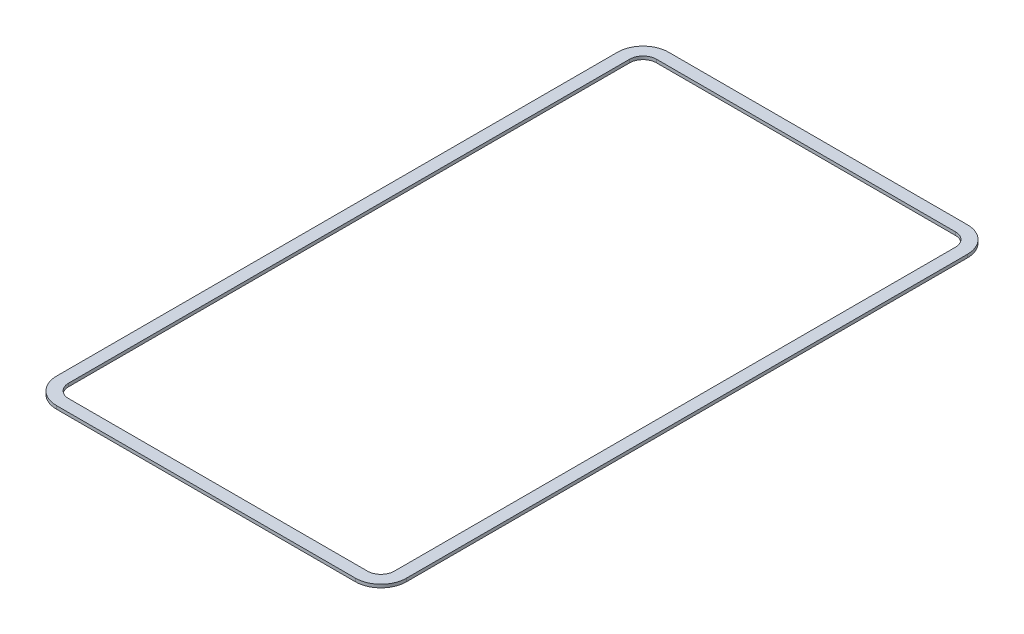
SolidWorks part; units mm, degrees
ref_plane "Front Plane" through (0, 0, 0) normal (0, 0, 1) x (1, 0, 0)
ref_plane "Top Plane" through (0, 0, 0) normal (0, 1, 0) x (1, 0, 0)
ref_plane "Right Plane" through (0, 0, 0) normal (1, 0, 0) x (0, 0, -1)
sketch "Sketch2" plane through (0, 0, 0) normal (0, 1, 0) x (1, 0, 0)
  line L0 (-117.8947, 9.4147) -> (13.1053, 9.4147) construction
  line L1 (-107.8947, 57.4147) -> (-61.0085, 57.4147)
  line L2 (-111.8947, 53.4147) -> (-111.8947, -34.5853)
  line L3 (-107.8947, -38.5853) -> (-61.0085, -38.5853)
  line L4 (-57.0085, 53.4147) -> (-57.0085, -34.5853)
  line L5 (-109.9947, 53.4147) -> (-109.9947, -34.5853)
  line L6 (-107.8947, -36.6853) -> (-61.0085, -36.6853)
  line L7 (-58.9085, 53.4147) -> (-58.9085, -34.5853)
  line L8 (-107.8947, 55.5147) -> (-61.0085, 55.5147)
  arc A0 (-111.8947, -34.5853) -> (-107.8947, -38.5853) centre (-107.8947, -34.5853) ccw
  arc A1 (-61.0085, -38.5853) -> (-57.0085, -34.5853) centre (-61.0085, -34.5853) ccw
  arc A2 (-61.0085, 57.4147) -> (-57.0085, 53.4147) centre (-61.0085, 53.4147) cw
  arc A3 (-107.8947, 57.4147) -> (-111.8947, 53.4147) centre (-107.8947, 53.4147) ccw
  arc A4 (-109.9947, -34.5853) -> (-107.8947, -36.6853) centre (-107.8947, -34.5853) ccw
  arc A5 (-61.0085, -36.6853) -> (-58.9085, -34.5853) centre (-61.0085, -34.5853) ccw
  arc A6 (-61.0085, 55.5147) -> (-58.9085, 53.4147) centre (-61.0085, 53.4147) cw
  arc A7 (-107.8947, 55.5147) -> (-109.9947, 53.4147) centre (-107.8947, 53.4147) ccw
  point P2 (-87.7113, 9.4147)
extrude "Boss-Extrude1" add sketch "Sketch2" along normal blind 0.5 contours L5 A4 L6 A5 L7 A6 L8 A7 | L1 A2 L4 A1 L3 A0 L2 A3
